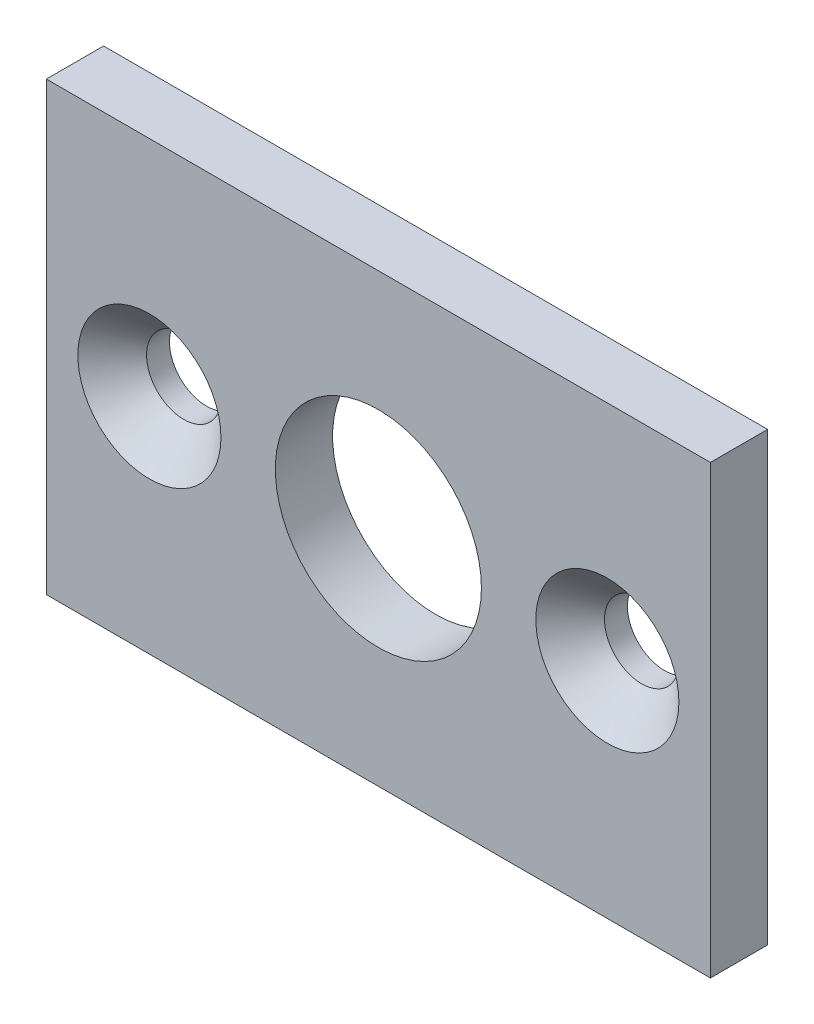
SolidWorks part; units mm, degrees
material "1.0037 (S235JR)"
ref_plane "Front Plane" through (0, 0, 0) normal (0, 0, 1) x (1, 0, 0)
ref_plane "Top Plane" through (0, 0, 0) normal (0, 1, 0) x (1, 0, 0)
ref_plane "Right Plane" through (0, 0, 0) normal (1, 0, 0) x (0, 0, -1)
sketch "Esquisse1" plane through (0, 0, 0) normal (0, 0, 1) x (1, 0, 0)
  line L1 (-29, 19.5) -> (29, 19.5)
  line L2 (-29, 19.5) -> (-29, -19.5)
  line L3 (-29, -19.5) -> (29, -19.5)
  line L4 (29, 19.5) -> (29, -19.5)
  line L5 (-29, 19.5) -> (29, -19.5) construction
  line L6 (-29, -19.5) -> (29, 19.5) construction
  circle A0 centre (0, 0) radius 9
  point P0 (0, 0)
  dimension "D3" = 18
  dimension "D1" = 39
  dimension "D2" = 58
extrude "Boss.-Extru.1" add sketch "Esquisse1" along normal blind 5
hole_wizard "Fraisage pour vis à tête fraisée à 6 pans creux M61" positions "Esquisse2" profile "Esquisse3" countersink size "M6" standard "ISO" end condition through all
sketch "Esquisse2" plane through (0, 0, 5) normal (0, 0, 1) x (1, 0, 0)
  line L0 (-29, -19.5) -> (29, -19.5) construction
  line L1 (29, -19.5) -> (29, 19.5) construction
  point P0 (20, 0)
  dimension "D1" = 19.5
  dimension "D2" = 9
sketch "Esquisse3" plane through (20, 0, 5) normal (1, 0, 0) x (0, -1, 0)
  line L0 (0, 0) -> (0, 5)
  line L1 (0, 5) -> (3.25, 5)
  line L2 (3.25, 5) -> (3.25, 3)
  line L3 (3.25, 3) -> (6.25, 0)
  line L5 (6.25, 0) -> (0, 0)
  line L6 (-3.25, 3) -> (-6.25, 0) construction
  line L11 (0, -6.35) -> (0, 107.95) construction
  dimension "Diamètre du perçage jusqu'au prochain" = 6.5
  dimension "Profondeur du perçage jusqu'au prochain" = 5
  dimension "Diamètre du fraisage entrant" = 12.5
  dimension "Angle du fraisage entrant" = 90
pattern_linear "Répétition linéaire1" count 2 spacing 40 along (-1, 0, 0) of "Fraisage pour vis à tête fraisée à 6 pans creux M61"
